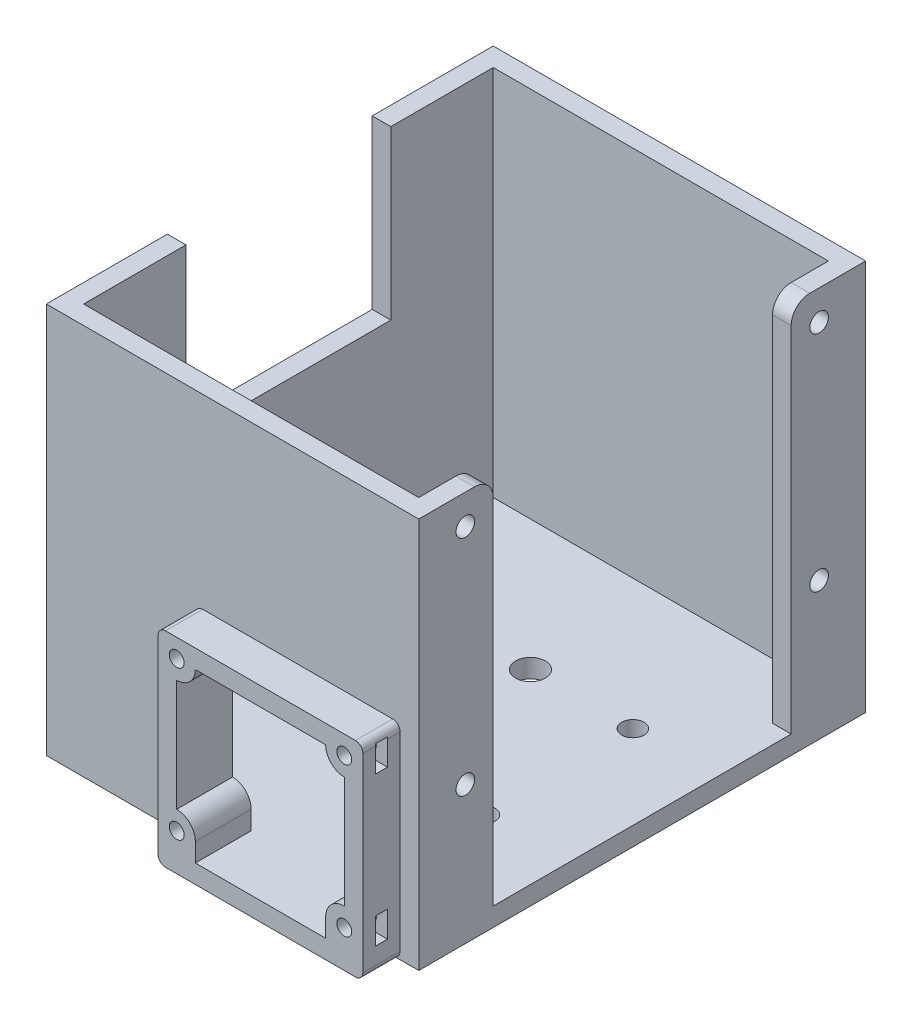
SolidWorks part; units mm, degrees
material "ABS"
ref_plane "Front" through (0, 0, 0) normal (0, 0, 1) x (1, 0, 0)
ref_plane "Top" through (0, 0, 0) normal (0, 1, 0) x (1, 0, 0)
ref_plane "Right" through (0, 0, 0) normal (1, 0, 0) x (0, 0, -1)
sketch "Croquis1" plane through (0, 0, 0) normal (0, 1, 0) x (1, 0, 0)
  line L1 (-50, -60) -> (50, -60)
  line L2 (-50, -60) -> (-50, 60)
  line L3 (-50, 60) -> (50, 60)
  line L4 (50, -60) -> (50, 60)
  line L5 (-50, -60) -> (50, 60) construction
  line L6 (-50, 60) -> (50, -60) construction
  point P0 (0, 0)
  dimension "D1" = 100
  dimension "D2" = 120
extrude "Saliente-Extruir1" add sketch "Croquis1" along normal blind 5
sketch "Croquis6" plane through (0, 0, 0) normal (0, 1, 0) x (1, 0, 0)
  line L1 (-27.5, 20) -> (27.5, 20) construction
  line L2 (-27.5, 20) -> (-27.5, -20) construction
  line L3 (-27.5, -20) -> (27.5, -20) construction
  line L4 (27.5, 20) -> (27.5, -20) construction
  line L5 (-27.5, 20) -> (27.5, -20) construction
  line L6 (-27.5, -20) -> (27.5, 20) construction
  circle A0 centre (27.5, -20) radius 3
  circle A1 centre (0, -20) radius 4
  circle A2 centre (-27.5, -20) radius 3
  circle A3 centre (-27.5, 20) radius 3
  circle A4 centre (0, 20) radius 4
  circle A5 centre (27.5, 20) radius 3
  point P0 (0, 0)
  dimension "D3" = 6
  dimension "D4" = 8
  dimension "D1" = 40
  dimension "D2" = 55
extrude "Cortar-Extruir5" cut sketch "Croquis6" along normal up to next
sketch "Croquis7" plane through (0, 5, 0) normal (0, 1, 0) x (1, 0, 0)
  line L0 (45, 40) -> (50, 40)
  line L1 (-50, -60) -> (50, -60)
  line L2 (-50, -60) -> (-50, 60)
  line L3 (-50, 60) -> (50, 60)
  line L4 (50, -60) -> (50, -40)
  line L5 (-50, -60) -> (50, 60) construction
  line L6 (-50, 60) -> (50, -60) construction
  line L7 (-45, -55) -> (45, -55)
  line L8 (-45, -55) -> (-45, 55)
  line L9 (-45, 55) -> (45, 55)
  line L10 (45, -55) -> (45, -40)
  line L11 (-45, -55) -> (45, 55) construction
  line L12 (-45, 55) -> (45, -55) construction
  line L13 (45, -40) -> (50, -40)
  line L14 (-57.75, 0) -> (57.75, 0) construction
  line L15 (45, 40) -> (45, 55)
  line L16 (50, 40) -> (50, 60)
  point P0 (0, 0)
  point P6 (0, 0)
  dimension "D1" = 5
  dimension "D2" = 5
  dimension "D3" = 80
  dimension "D4" = 40
extrude "Saliente-Extruir2" add sketch "Croquis7" along normal blind 100
sketch "Croquis8" plane through (50, 0, 0) normal (1, 0, 0) x (0, 0, -1)
  line L0 (-60, 105) -> (-40, 105) construction
  line L1 (-27.5, 105) -> (27.5, 105)
  line L2 (-27.5, 105) -> (-27.5, 60)
  line L3 (-27.5, 60) -> (27.5, 60)
  line L4 (27.5, 105) -> (27.5, 60)
  line L5 (0, 57.75) -> (0, -57.75) construction
  point P7 (0, 105)
  dimension "D1" = 55
  dimension "D2" = 45
extrude "Cortar-Extruir6" cut sketch "Croquis8" against normal through all
sketch "Croquis12" plane through (0, 0, 60) normal (0, 0, 1) x (1, 0, 0)
  line L0 (-50, 0) -> (50, 0) construction
  line L1 (0, 5) -> (35, 5)
  line L2 (-5, 15) -> (-5, 45)
  line L3 (0, 50) -> (35, 50)
  line L4 (40, 15) -> (40, 45)
  line L5 (-5, 5) -> (40, 50) construction
  line L6 (-5, 50) -> (40, 5) construction
  line L7 (50, 105) -> (50, 0) construction
  line L8 (35, 10) -> (35, 5)
  line L9 (0, 10) -> (0, 5)
  arc A0 (-5, 45) -> (0, 50) centre (-5, 50) ccw
  arc A1 (35, 50) -> (40, 45) centre (40, 50) ccw
  arc A2 (0, 10) -> (-5, 15) centre (-5, 10) ccw
  arc A3 (40, 15) -> (35, 10) centre (40, 10) ccw
  point P0 (17.5, 27.5)
  dimension "D5" = 10
  dimension "D1" = 5
  dimension "D2" = 10
  dimension "D3" = 45
  dimension "D4" = 45
  dimension "D6" = 5
extrude "Cortar-Extruir8" cut sketch "Croquis12" against normal up to next
sketch "Croquis13" plane through (0, 0, 60) normal (0, 0, 1) x (1, 0, 0)
  line L0 (0, 5) -> (35, 5) construction
  line L1 (-5, 45) -> (-5, 15) construction
  line L2 (0, 10) -> (0, 5) construction
  line L3 (35, 5) -> (35, 10) construction
  line L4 (40, 15) -> (40, 45) construction
  line L5 (35, 50) -> (0, 50) construction
  line L6 (0, 5) -> (35, 5)
  line L7 (-5, 45) -> (-5, 15)
  line L8 (0, 10) -> (0, 5)
  line L9 (35, 5) -> (35, 10)
  line L10 (40, 15) -> (40, 45)
  line L11 (35, 50) -> (0, 50)
  line L12 (-50, 0) -> (50, 0) construction
  line L13 (-8, 0) -> (43, 0)
  line L14 (-10, 2) -> (-10, 53)
  line L15 (-8, 55) -> (43, 55)
  line L16 (45, 2) -> (45, 53)
  line L17 (-10, 0) -> (45, 55) construction
  line L18 (-10, 55) -> (45, 0) construction
  arc A0 (-5, 45) -> (0, 50) centre (-5, 50) ccw construction
  arc A1 (0, 10) -> (-5, 15) centre (-5, 10) ccw construction
  arc A2 (40, 15) -> (35, 10) centre (40, 10) ccw construction
  arc A3 (35, 50) -> (40, 45) centre (40, 50) ccw construction
  arc A4 (-5, 45) -> (0, 50) centre (-5, 50) ccw
  arc A5 (0, 10) -> (-5, 15) centre (-5, 10) ccw
  arc A6 (40, 15) -> (35, 10) centre (40, 10) ccw
  arc A7 (35, 50) -> (40, 45) centre (40, 50) ccw
  arc A8 (-8, 0) -> (-10, 2) centre (-8, 2) cw
  arc A9 (43, 0) -> (45, 2) centre (43, 2) ccw
  arc A10 (43, 55) -> (45, 53) centre (43, 53) cw
  arc A11 (-10, 53) -> (-8, 55) centre (-8, 53) cw
  circle A12 centre (-5, 50) radius 2
  circle A13 centre (40, 50) radius 2
  circle A14 centre (40, 10) radius 2
  circle A15 centre (-5, 10) radius 2
  point P5 (17.5, 27.5)
  point P21 (17.5, 0)
  point P22 (17.5, 5)
  dimension "D3" = 2
  dimension "D4" = 4
  dimension "D1" = 55
  dimension "D2" = 55
extrude "Saliente-Extruir4" add sketch "Croquis13" along normal blind 10
ref_plane "Plano1" through (0, 0, 65) normal (0, 0, 1) x (1, 0, 0)
sketch "Croquis15" plane through (0, 0, 65) normal (0, 0, 1) x (1, 0, 0)
  line L0 (42.0207, 53.5) -> (45, 53.5)
  line L1 (-0.9585, 50) -> (-2.9793, 53.5)
  line L2 (-2.9793, 53.5) -> (-7.0207, 53.5)
  line L3 (-7.0207, 53.5) -> (-9.0415, 50) construction
  line L4 (-9.0415, 50) -> (-7.0207, 46.5) construction
  line L5 (-7.0207, 46.5) -> (-2.9793, 46.5)
  line L6 (-2.9793, 46.5) -> (-0.9585, 50)
  line L7 (35.9585, 50) -> (37.9793, 46.5)
  line L8 (37.9793, 46.5) -> (42.0207, 46.5)
  line L9 (42.0207, 46.5) -> (44.0415, 50) construction
  line L10 (44.0415, 50) -> (42.0207, 53.5) construction
  line L11 (42.0207, 53.5) -> (37.9793, 53.5)
  line L12 (37.9793, 53.5) -> (35.9585, 50)
  line L13 (35.9585, 10) -> (37.9793, 6.5)
  line L14 (37.9793, 6.5) -> (42.0207, 6.5)
  line L15 (42.0207, 6.5) -> (44.0415, 10) construction
  line L16 (44.0415, 10) -> (42.0207, 13.5) construction
  line L17 (42.0207, 13.5) -> (37.9793, 13.5)
  line L18 (37.9793, 13.5) -> (35.9585, 10)
  line L19 (-0.9585, 10) -> (-2.9793, 13.5)
  line L20 (-2.9793, 13.5) -> (-7.0207, 13.5)
  line L21 (-7.0207, 13.5) -> (-9.0415, 10) construction
  line L22 (-9.0415, 10) -> (-7.0207, 6.5) construction
  line L23 (-7.0207, 6.5) -> (-2.9793, 6.5)
  line L24 (-2.9793, 6.5) -> (-0.9585, 10)
  line L25 (45, 53.5) -> (45, 46.5)
  line L26 (45, 2) -> (45, 53) construction
  line L27 (45, 46.5) -> (42.0207, 46.5)
  line L28 (-7.0207, 53.5) -> (-10, 53.5)
  line L29 (-10, 53.5) -> (-10, 46.5)
  line L30 (-10, 53) -> (-10, 2) construction
  line L31 (-10, 46.5) -> (-7.0207, 46.5)
  line L32 (-7.0207, 13.5) -> (-10, 13.5)
  line L33 (-10, 53) -> (-10, 2) construction
  line L34 (-10, 13.5) -> (-10, 6.5)
  line L35 (-10, 6.5) -> (-7.0207, 6.5)
  line L36 (42.0207, 13.5) -> (45, 13.5)
  line L37 (45, 2) -> (45, 53) construction
  line L38 (45, 13.5) -> (45, 6.5)
  line L39 (45, 6.5) -> (42.0207, 6.5)
  circle A0 centre (-5, 50) radius 3.5 construction
  circle A1 centre (40, 50) radius 3.5 construction
  circle A2 centre (40, 10) radius 3.5 construction
  circle A3 centre (-5, 10) radius 3.5 construction
  dimension "D1" = 7
extrude "Cortar-Extruir9" cut sketch "Croquis15" against normal mid plane 3.2
sketch "Croquis16" plane through (50, 0, 0) normal (1, 0, 0) x (0, 0, -1)
  line L0 (0, 57.75) -> (0, -57.75) construction
  line L1 (-47.5, 37) -> (47.5, 37) construction
  line L2 (-47.5, 37) -> (-47.5, 97) construction
  line L3 (-47.5, 97) -> (47.5, 97) construction
  line L4 (47.5, 37) -> (47.5, 97) construction
  line L5 (-47.5, 37) -> (47.5, 97) construction
  line L6 (-47.5, 97) -> (47.5, 37) construction
  line L7 (-60, 105) -> (-40, 105) construction
  circle A0 centre (-47.5, 97) radius 2.5
  circle A1 centre (-47.5, 37) radius 2.5
  circle A2 centre (47.5, 97) radius 2.5
  circle A3 centre (47.5, 37) radius 2.5
  point P8 (0, 67)
  dimension "D1" = 5
  dimension "D2" = 60
  dimension "D3" = 95
  dimension "D4" = 8
extrude "Cortar-Extruir10" cut sketch "Croquis16" against normal up to next
fillet "Redondeo1" radius 5 2 edges at (47.5, 105, 40) (47.5, 105, -40)
sketch "Croquis17" plane through (0, 0, 0) normal (1, 0, 0) x (0, 0, -1)
  line L0 (0, 85) -> (21.8061, 85) construction
  line L1 (0, 57.75) -> (0, -57.75) construction
  line L2 (0, 85) -> (0, 107.4622) construction
  line L3 (27.5, 60) -> (-27.5, 60) construction
  dimension "D1" = 25
